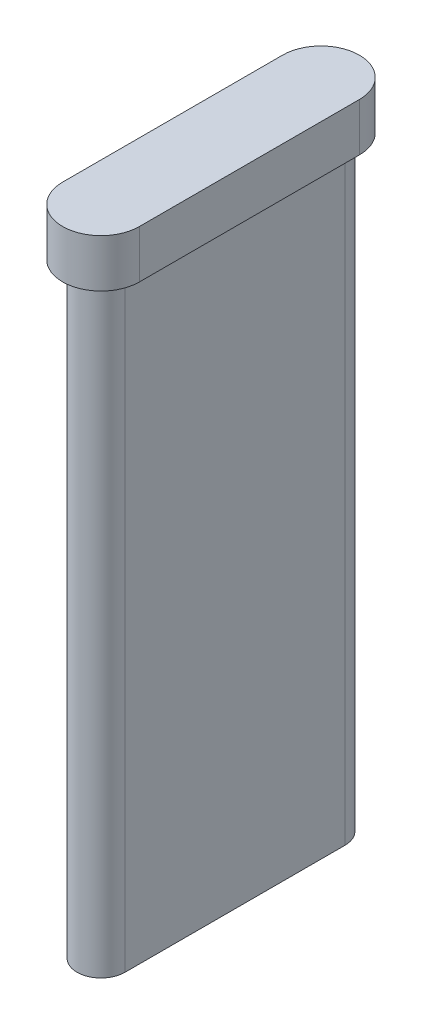
SolidWorks part; units mm, degrees
material "K110"
ref_plane "Front Plane" through (0, 0, 0) normal (0, 0, 1) x (1, 0, 0)
ref_plane "Top Plane" through (0, 0, 0) normal (0, 1, 0) x (1, 0, 0)
ref_plane "Right Plane" through (0, 0, 0) normal (1, 0, 0) x (0, 0, -1)
sketch "Sketch1" plane through (0, 0, 0) normal (0, 1, 0) x (1, 0, 0)
  line L0 (0, -11.45) -> (0, 11.45) construction
  line L1 (-2.5, -11.45) -> (-2.5, 11.45)
  line L2 (2.5, -11.45) -> (2.5, 11.45)
  arc A0 (-2.5, -11.45) -> (2.5, -11.45) centre (0, -11.45) ccw
  arc A1 (2.5, 11.45) -> (-2.5, 11.45) centre (0, 11.45) ccw
  point P2 (0, 0)
  dimension "D2" = 2.5
  dimension "D1" = 22.9
extrude "Boss-Extrude1" add sketch "Sketch1" against normal blind 68
sketch "Sketch2" plane through (0, 0, 0) normal (0, 1, 0) x (1, 0, 0)
  line L4 (4, -11.45) -> (4, 11.45)
  line L5 (-4, 11.45) -> (-4, -11.45)
  line L6 (4, -11.45) -> (4, 11.45)
  line L7 (-4, 11.45) -> (-4, -11.45)
  arc A4 (4, 11.45) -> (-4, 11.45) centre (0, 11.45) ccw
  arc A5 (-4, -11.45) -> (4, -11.45) centre (0, -11.45) ccw
  arc A6 (4, 11.45) -> (-4, 11.45) centre (0, 11.45) ccw
  arc A7 (-4, -11.45) -> (4, -11.45) centre (0, -11.45) ccw
  dimension "D1" = 1.5
extrude "Boss-Extrude2" add sketch "Sketch2" against normal blind 5
